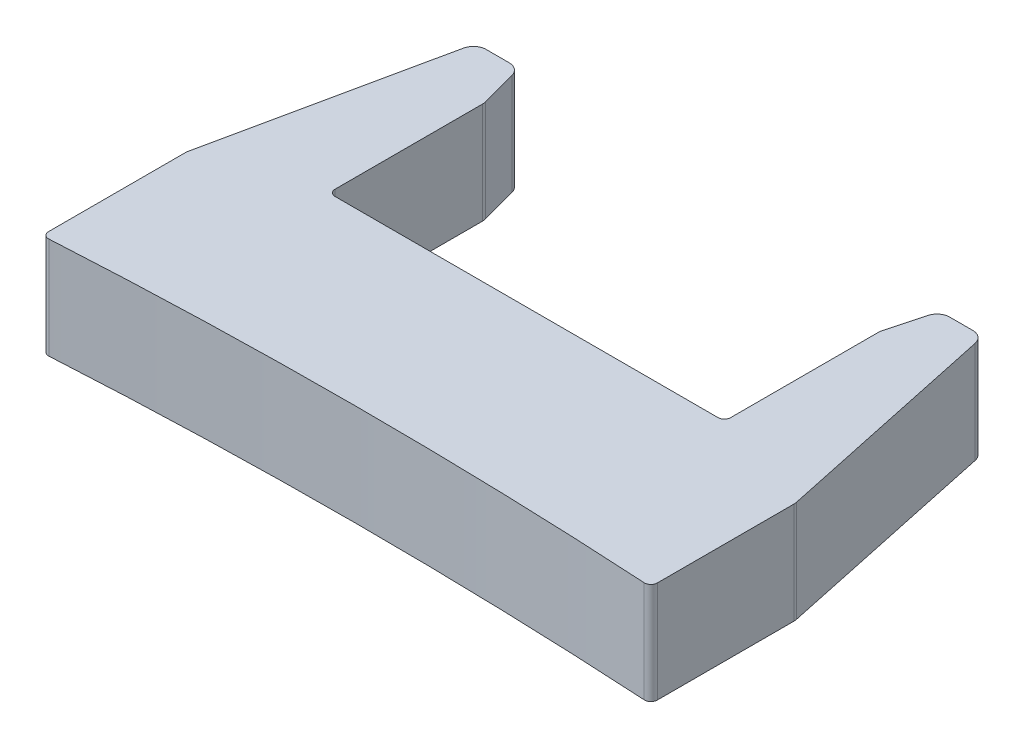
SolidWorks part; units mm, degrees
material "6061-T6 (SS)"
ref_plane "Front Plane" through (0, 0, 0) normal (0, 0, 1) x (1, 0, 0)
ref_plane "Top Plane" through (0, 0, 0) normal (0, 1, 0) x (1, 0, 0)
ref_plane "Right Plane" through (0, 0, 0) normal (1, 0, 0) x (0, 0, -1)
sketch "Sketch1" plane through (0, 0, 0) normal (0, 1, 0) x (1, 0, 0)
  line L0 (-20, 0) -> (0, 0)
  line L1 (24, -2.8) -> (24, -14.2206)
  line L2 (-24, -2.8) -> (-24, -14.2206)
  line L3 (-24, -13.5) -> (24, -13.5) construction
  line L4 (-20, 0) -> (-20, -2.8)
  line L5 (-20, -2.8) -> (-24, -2.8)
  line L6 (20, 0) -> (20, -2.8)
  line L7 (20, -2.8) -> (24, -2.8)
  line L22 (0, 0) -> (20, 0)
  line L25 (-24, -14.2206) -> (0, -413.5) construction
  line L26 (0, -413.5) -> (24, -14.2206) construction
  arc A0 (-24, -14.2206) -> (24, -14.2206) centre (0, -413.5) cw
  dimension "D1" = 13.5
  dimension "D2" = 400
  dimension "D3" = 2.8
  dimension "D4" = 20
  dimension "D5" = 48
extrude "Boss-Extrude1" add sketch "Sketch1" along normal mid plane 8
sketch "Sketch5" plane through (0, 4, 0) normal (0, 1, 0) x (1, 0, 0)
  line L4 (-20, 0) -> (-20, 16) construction
  line L5 (0, 0) -> (0, 18.0283) construction
  line L8 (20, 0) -> (20, 16) construction
  line L17 (-20, 16) -> (-15.6, 16)
  line L19 (-15.6, 16) -> (-15.6, 0)
  line L20 (20, 0) -> (-20, 0) construction
  line L22 (-15.6, 0) -> (-20, 0)
  line L24 (-20, 16) -> (-24, -2.8)
  line L25 (-24, -2.8) -> (-20, -2.8)
  line L26 (-20, -2.8) -> (-20, 0)
  line L27 (20, -2.8) -> (20, 0)
  line L28 (24, -2.8) -> (20, -2.8)
  line L29 (20, 16) -> (24, -2.8)
  line L30 (15.6, 0) -> (20, 0)
  line L31 (15.6, 16) -> (15.6, 0)
  line L32 (20, 16) -> (15.6, 16)
  dimension "D1" = 4.4
  dimension "D2" = 16
extrude "Boss-Extrude2" add sketch "Sketch5" against normal up to surface (8 mm away) up to face at (0, -4, 4.8651)
hole_wizard "M6x1.0 Tapped Hole1" positions "Sketch4" profile "Sketch3" tap size "M6x1.0" standard "ANSI Metric"
sketch "Sketch4" plane through (0, 0, 0) normal (0, 0, -1) x (-1, 0, 0)
  point P0 (0, 0)
cosmetic thread "Hole Thread1" parameters "D1"=6, "D2"=6
sketch "Sketch3" plane through (0, 0, 0) normal (1, 0, 0) x (0, 1, 0)
  line L0 (0, 0) -> (0, 12.5022)
  line L1 (0, 12.5022) -> (2.5, 11)
  line L2 (2.5, 11) -> (2.5, 0)
  line L5 (2.5, 0) -> (0, 0)
  line L10 (0, 12.5022) -> (-2.5, 11) construction
  line L11 (0, -6.35) -> (0, 107.95) construction
  dimension "Tap Drill Dia." = 5
  dimension "Tap Drill Depth" = 11
  dimension "Drill Angle" = 118
chamfer "Chamfer1" distance 1 angle 75 2 edges at (-15.6, 0, -16) (15.6, 0, -16)
fillet "Fillet1" radius 1 8 edges at (-15.6, 0, -12.2679) (-16.6, 0, -16) (20, 0, -16) (24, 0, 2.8) (-24, 0, 2.8) (-20, 0, -16) (16.6, 0, -16) (15.6, 0, -12.2679)
fillet "Fillet2" radius 0.5 4 edges at (-24, 0, 14.2206) (24, 0, 14.2206) (-15.6, 0, 0) (15.6, 0, 0)
sketch "Sketch7" plane through (0, 4, 0) normal (0, 1, 0) x (1, 0, 0)
  line L0 (15.4536, 0.1464) -> (16.2036, 0.1464)
  line L1 (-15.4536, 0.1464) -> (-16.2036, 0.1464)
  arc A0 (15.1, 0) -> (15.6, 0.5) centre (15.1, 0.5) ccw construction
  arc A1 (-15.6, 0.5) -> (-15.1, 0) centre (-15.1, 0.5) ccw construction
  point P11 (-16.2036, 0.1464)
  point P12 (16.2036, 0.1464)
  dimension "D1" = 0.75
  dimension "D2" = 0.75
